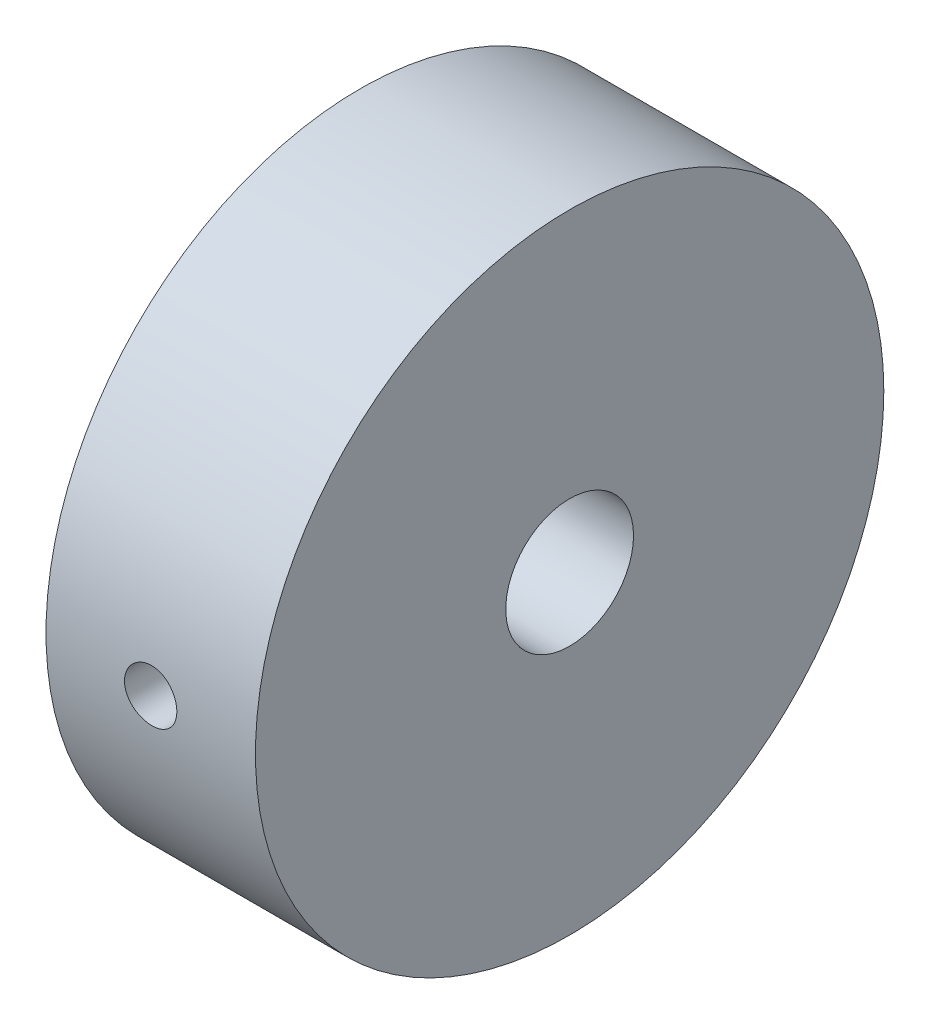
SolidWorks part; units mm, degrees
ref_plane "Plan de face" through (0, 0, 0) normal (0, 0, 1) x (1, 0, 0)
ref_plane "Plan de dessus" through (0, 0, 0) normal (0, 1, 0) x (1, 0, 0)
ref_plane "Plan de droite" through (0, 0, 0) normal (1, 0, 0) x (0, 0, -1)
sketch "Esquisse1" plane through (0, 0, 0) normal (1, 0, 0) x (0, 0, -1)
  circle A0 centre (0, 0) radius 15
  circle A1 centre (0, 0) radius 3.05
  dimension "D1" = 30
  dimension "D2" = 6.1
extrude "Boss.-Extru.1" add sketch "Esquisse1" along normal blind 10
hole_wizard "Trou taraudé M31" positions "Esquisse3D2" profile "Esquisse3" tap size "M3" standard "ISO"
sketch3d "Esquisse3D2"
  point P0 (4.9956, -0.1231, 14.9995)
  dimension "D1" = 15.81
sketch "Esquisse3" plane through (4.9956, -0.1231, 14.9995) normal (1, 0, 0) x (0, -1, -0.0082)
  line L0 (0, 0) -> (0, 11.95)
  line L1 (0, 11.95) -> (1.25, 11.95)
  line L2 (1.25, 11.95) -> (1.25, 0)
  line L5 (1.25, 0) -> (0, 0)
  line L11 (0, -6.35) -> (0, 107.95) construction
  dimension "Diamètre du trou pour taraudage jusqu'au prochain" = 2.5
  dimension "Profondeur du trou pour taraudage jusqu'au prochain" = 11.95
cosmetic thread "Filetage de perçage1" parameters "D2"=3
